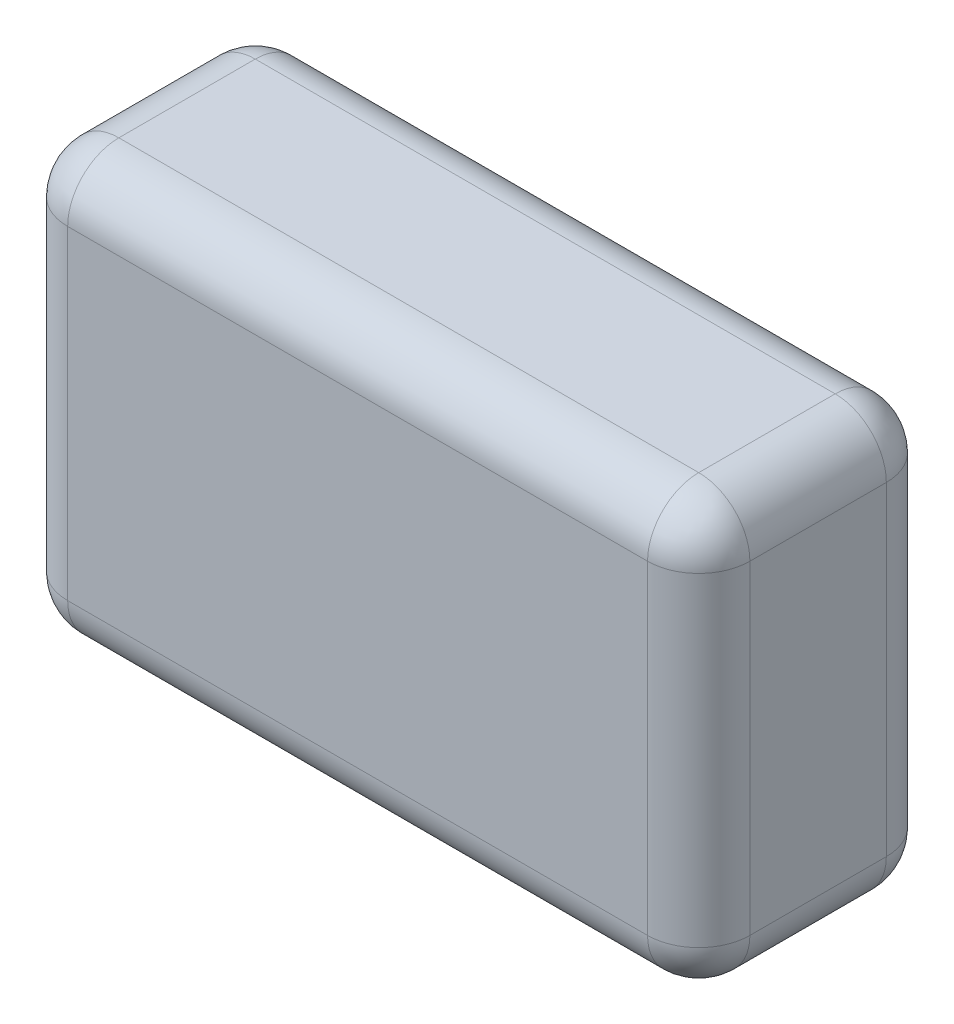
SolidWorks part; units mm, degrees
ref_plane "Front Plane" through (0, 0, 0) normal (0, 0, 1) x (1, 0, 0)
ref_plane "Top Plane" through (0, 0, 0) normal (0, 1, 0) x (1, 0, 0)
ref_plane "Right Plane" through (0, 0, 0) normal (1, 0, 0) x (0, 0, -1)
sketch "Sketch1" plane through (0, 0, 0) normal (0, 1, 0) x (1, 0, 0)
  line L1 (-20, 7) -> (20, 7)
  line L2 (-20, 7) -> (-20, -7)
  line L3 (-20, -7) -> (20, -7)
  line L4 (20, 7) -> (20, -7)
  line L5 (-20, 7) -> (20, -7) construction
  line L6 (-20, -7) -> (20, 7) construction
  point P0 (0, 0)
  dimension "D1" = 14
  dimension "D2" = 40
extrude "Boss-Extrude1" add sketch "Sketch1" along normal blind 25
fillet "Fillet1" radius 3 12 edges at (0, 0, 7) (20, 0, 0) (20, 12.5, -7) (0, 25, -7) (0, 0, -7) (-20, 12.5, -7) (-20, 25, 0) (-20, 12.5, 7) (-20, 0, 0) (20, 12.5, 7) (20, 25, 0) (0, 25, 7)
